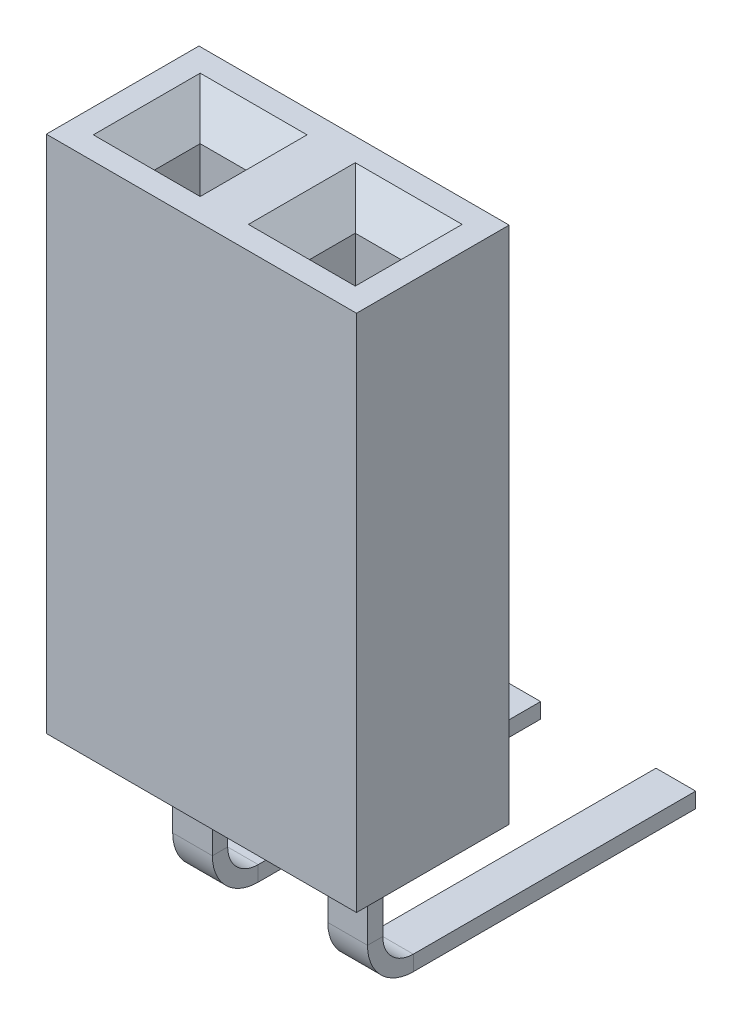
SolidWorks part; units mm, degrees
material "ABS"
ref_plane "Front Plane" through (0, 0, 0) normal (0, 0, 1) x (1, 0, 0)
ref_plane "Top Plane" through (0, 0, 0) normal (0, 1, 0) x (1, 0, 0)
ref_plane "Right Plane" through (0, 0, 0) normal (1, 0, 0) x (0, 0, -1)
sketch "Sketch1" plane through (0, 0, 0) normal (0, 1, 0) x (1, 0, 0)
  line L0 (-1.27, 0) -> (0, 0) construction
  line L1 (-2.54, 1.25) -> (2.54, 1.25)
  line L2 (-2.54, 1.25) -> (-2.54, -1.25)
  line L3 (-2.54, -1.25) -> (2.54, -1.25)
  line L4 (2.54, 1.25) -> (2.54, -1.25)
  line L5 (-2.54, 1.25) -> (2.54, -1.25) construction
  line L6 (-2.54, -1.25) -> (2.54, 1.25) construction
  line L7 (-1.645, 0.375) -> (-0.895, 0.375)
  line L8 (-1.645, 0.375) -> (-1.645, -0.375)
  line L9 (-1.645, -0.375) -> (-0.895, -0.375)
  line L10 (-0.895, 0.375) -> (-0.895, -0.375)
  line L11 (-1.645, 0.375) -> (-0.895, -0.375) construction
  line L12 (-1.645, -0.375) -> (-0.895, 0.375) construction
  line L13 (0.895, 0.375) -> (1.645, 0.375)
  line L14 (0.895, 0.375) -> (0.895, -0.375)
  line L15 (0.895, -0.375) -> (1.645, -0.375)
  line L16 (1.645, 0.375) -> (1.645, -0.375)
  line L17 (0.895, 0.375) -> (1.645, -0.375) construction
  line L18 (0.895, -0.375) -> (1.645, 0.375) construction
  line L19 (0, 0) -> (1.27, 0) construction
  point P0 (0, 0)
  point P6 (-1.27, 0)
  point P11 (1.27, 0)
  dimension "D1" = 2.5
  dimension "D2" = 5.08
  dimension "D3" = 2.54
  dimension "D4" = 0.75
extrude "Boss-Extrude1" add sketch "Sketch1" along normal blind 8.5
chamfer "Chamfer1" distance 0.5 angle 45 8 edges at (1.645, 8.5, 0) (1.27, 8.5, 0.375) (0.895, 8.5, 0) (1.27, 8.5, -0.375) (-1.27, 8.5, 0.375) (-0.895, 8.5, 0) (-1.27, 8.5, -0.375) (-1.645, 8.5, 0)
sketch "Sketch2" plane through (0, 0, 0) normal (0, -1, 0) x (1, 0, 0)
  line L0 (-1.645, 0.375) -> (-0.895, -0.375) construction
  line L1 (-1.595, 0.125) -> (-0.945, 0.125)
  line L2 (-1.595, 0.125) -> (-1.595, -0.125)
  line L3 (-1.595, -0.125) -> (-0.945, -0.125)
  line L4 (-0.945, 0.125) -> (-0.945, -0.125)
  line L5 (-1.595, 0.125) -> (-0.945, -0.125) construction
  line L6 (-1.595, -0.125) -> (-0.945, 0.125) construction
  line L7 (0.945, 0.125) -> (1.595, 0.125)
  line L8 (0.945, 0.125) -> (0.945, -0.125)
  line L9 (0.945, -0.125) -> (1.595, -0.125)
  line L10 (1.595, 0.125) -> (1.595, -0.125)
  line L11 (0.945, 0.125) -> (1.595, -0.125) construction
  line L12 (0.945, -0.125) -> (1.595, 0.125) construction
  line L13 (-1.645, -0.375) -> (-0.895, 0.375) construction
  line L14 (0.895, 0.375) -> (1.645, -0.375) construction
  line L15 (0.895, -0.375) -> (1.645, 0.375) construction
  point P0 (-1.27, 0)
  point P5 (1.27, 0)
  dimension "D1" = 0.25
  dimension "D2" = 0.65
sketch "Sketch3" plane through (-2.54, 0, 0) normal (-1, 0, 0) x (0, 0, 1)
  line L0 (-0.125, 0) -> (-0.125, -1.5)
  line L1 (0.125, 0) -> (-0.125, 0) construction
  line L2 (-0.625, -2) -> (-5.25, -2)
  line L3 (-1.25, 0) -> (1.25, 0) construction
  line L4 (-1.25, 8.5) -> (-1.25, 0) construction
  arc A0 (-0.125, -1.5) -> (-0.625, -2) centre (-0.625, -1.5) cw
  dimension "D1" = 0.5
  dimension "D2" = 2
  dimension "D3" = 4
sweep "Sweep1" add profiles "Sketch2" path "Sketch3"
ref_point "EAGLEREF"
